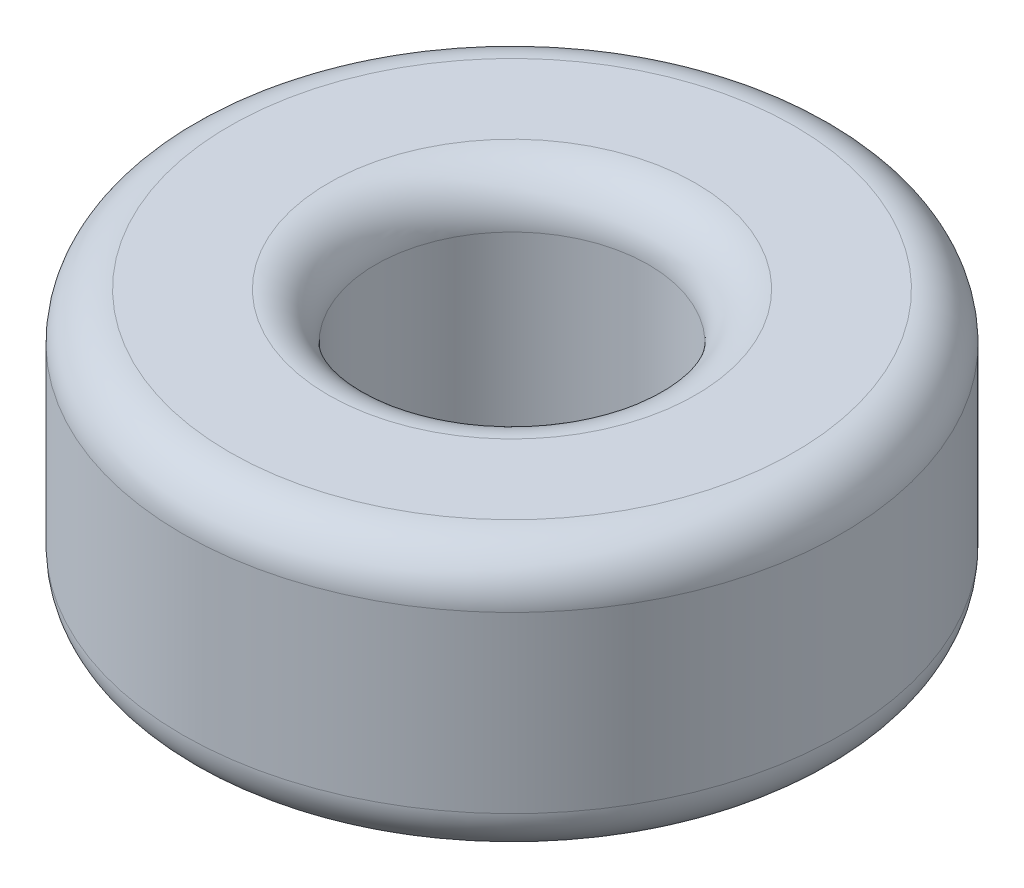
SolidWorks part; units mm, degrees
ref_plane "Front Plane" through (0, 0, 0) normal (0, 0, 1) x (1, 0, 0)
ref_plane "Top Plane" through (0, 0, 0) normal (0, 1, 0) x (1, 0, 0)
ref_plane "Right Plane" through (0, 0, 0) normal (1, 0, 0) x (0, 0, -1)
sketch "Sketch1" plane through (0, 0, 0) normal (0, 1, 0) x (1, 0, 0)
  circle A0 centre (0, 0) radius 70
  circle A1 centre (0, 0) radius 29
extrude "Boss-Extrude1" add sketch "Sketch1" along normal blind 57
fillet "Fillet1" radius 10 1 edges at (0, 57, 70)
fillet "Fillet2" radius 10 1 edges at (0, 0, 70)
fillet "Fillet3" radius 10 1 edges at (0, 57, 29)
fillet "Fillet4" radius 10 1 edges at (0, 0, 29)
